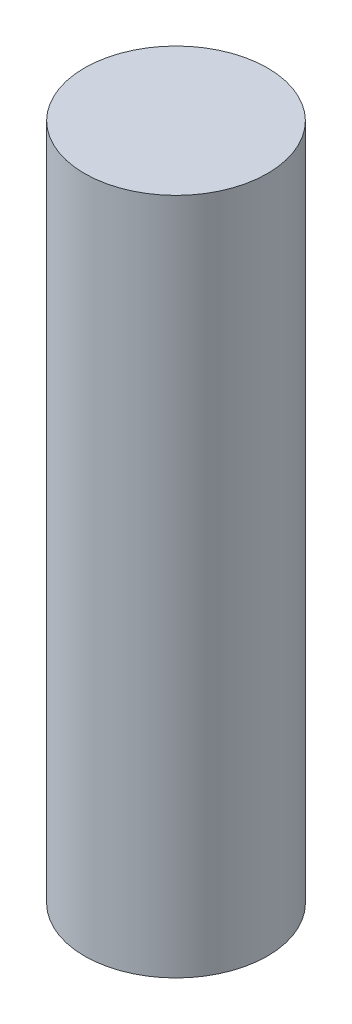
SolidWorks part; units mm, degrees
ref_plane "Front Plane" through (0, 0, 0) normal (0, 0, 1) x (1, 0, 0)
ref_plane "Top Plane" through (0, 0, 0) normal (0, 1, 0) x (1, 0, 0)
ref_plane "Right Plane" through (0, 0, 0) normal (1, 0, 0) x (0, 0, -1)
sketch "Sketch1" plane through (0, 0, 0) normal (0, 0, 1) x (1, 0, 0)
  line L0 (0, 0) -> (0, 50)
  point P6 (0, 50)
  dimension "D2" = 50
sketch "Sketch2" plane through (0, 0, 0) normal (0, 1, 0) x (1, 0, 0)
  circle A0 centre (0, 0) radius 6.75
  dimension "D1" = 13.5
sweep "Sweep1" add profiles "Sketch2" path "Sketch1"
